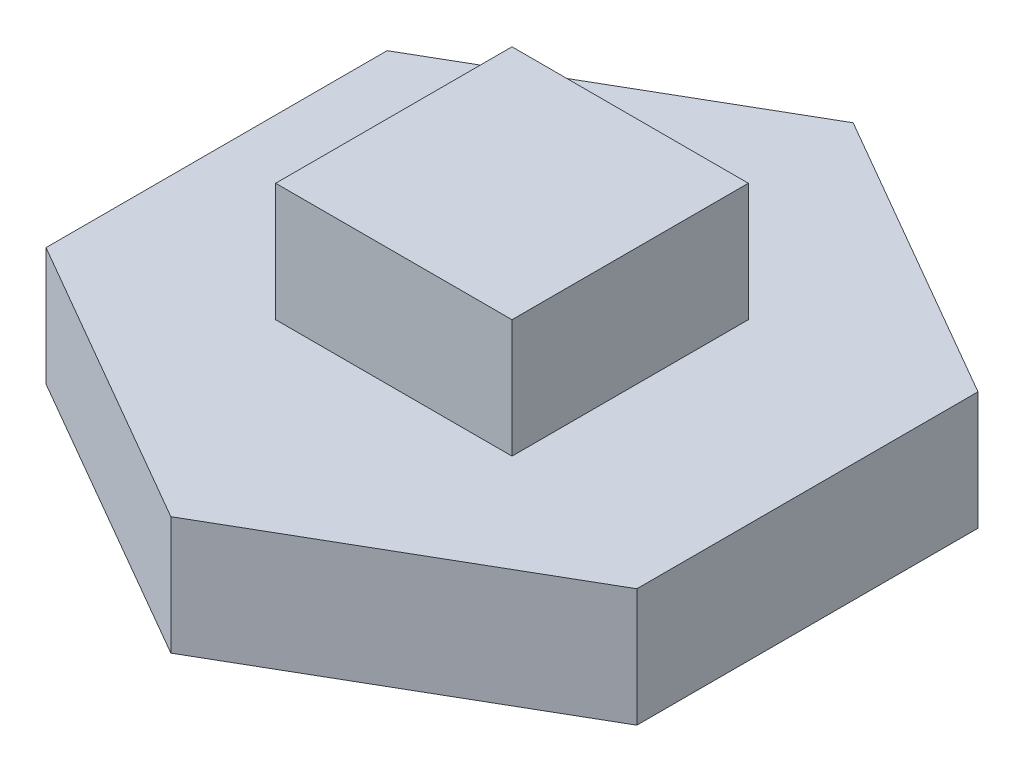
SolidWorks part; units mm, degrees
ref_plane "前视基准面" through (0, 0, 0) normal (0, 0, 1) x (1, 0, 0)
ref_plane "上视基准面" through (0, 0, 0) normal (0, 1, 0) x (1, 0, 0)
ref_plane "右视基准面" through (0, 0, 0) normal (1, 0, 0) x (0, 0, -1)
sketch "草图1" plane through (0, 0, 0) normal (0, 1, 0) x (1, 0, 0)
  line L1 (25, 14.4338) -> (0, 28.8675)
  line L2 (0, 28.8675) -> (-25, 14.4338)
  line L3 (-25, 14.4338) -> (-25, -14.4338)
  line L4 (-25, -14.4338) -> (0, -28.8675)
  line L5 (0, -28.8675) -> (25, -14.4338)
  line L6 (25, -14.4338) -> (25, 14.4338)
  circle A0 centre (0, 0) radius 25 construction
extrude "凸台-拉伸1" add sketch "草图1" along normal blind 10
sketch "草图2" plane through (0, 10, 0) normal (0, 1, 0) x (1, 0, 0)
  line L1 (-10, 10) -> (10, 10)
  line L2 (-10, 10) -> (-10, -10)
  line L3 (-10, -10) -> (10, -10)
  line L4 (10, 10) -> (10, -10)
  line L5 (-10, 10) -> (10, -10) construction
  line L6 (-10, -10) -> (10, 10) construction
  point P0 (0, 0)
  dimension "D1" = 20
  dimension "D2" = 20
extrude "凸台-拉伸2" add sketch "草图2" along normal blind 10
